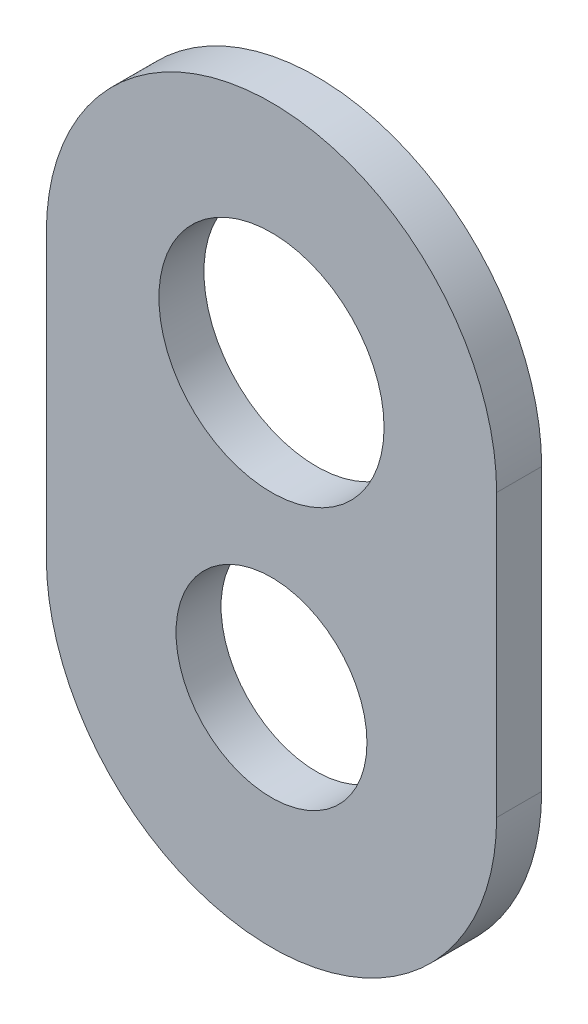
SolidWorks part; units mm, degrees
material "6061-T6 (SS)"
ref_plane "Front Plane" through (0, 0, 0) normal (0, 0, 1) x (1, 0, 0)
ref_plane "Top Plane" through (0, 0, 0) normal (0, 1, 0) x (1, 0, 0)
ref_plane "Right Plane" through (0, 0, 0) normal (1, 0, 0) x (0, 0, -1)
sketch "Sketch1" plane through (0, 0, 0) normal (0, 0, 1) x (1, 0, 0)
  line L0 (-25.4, 0) -> (-25.4, -31.75)
  line L1 (25.4, 0) -> (25.4, -31.75)
  circle A0 centre (0, 0) radius 12.7
  circle A2 centre (0, -31.75) radius 10.7696
  arc A3 (-25.4, -31.75) -> (25.4, -31.75) centre (0, -31.75) ccw
  arc A4 (25.4, 0) -> (-25.4, 0) centre (0, 0) ccw
  dimension "D1" = 25.4
  dimension "D2" = 50.8
  dimension "D4" = 50.8
  dimension "D5" = 21.5392
  dimension "D3" = 31.75
extrude "Boss-Extrude1" add sketch "Sketch1" along normal blind 5.08
